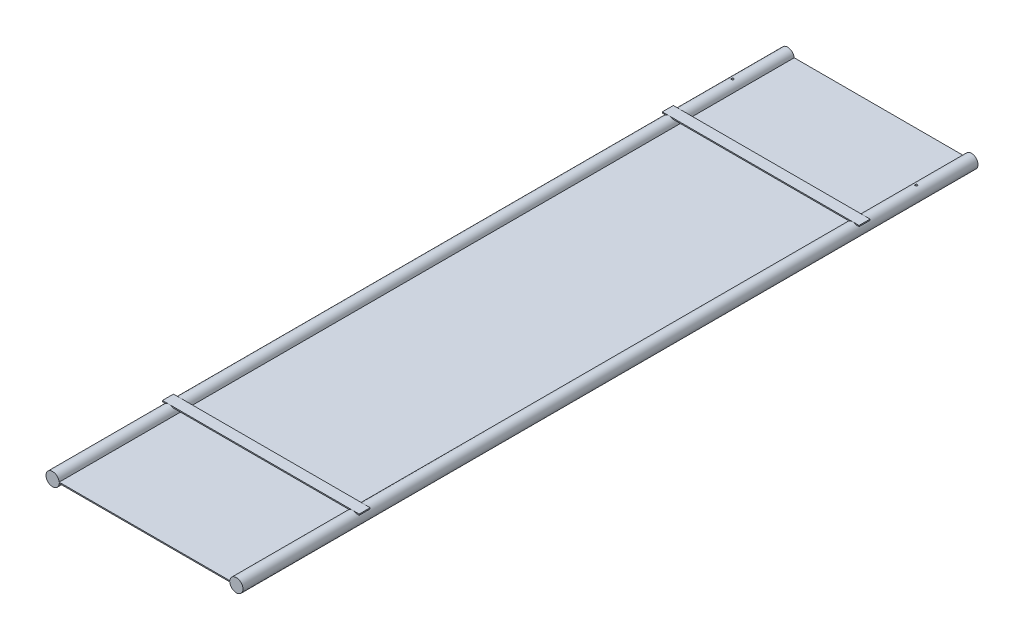
SolidWorks part; units mm, degrees
ref_plane "前视基准面" through (0, 0, 0) normal (0, 0, 1) x (1, 0, 0)
ref_plane "上视基准面" through (0, 0, 0) normal (0, 1, 0) x (1, 0, 0)
ref_plane "右视基准面" through (0, 0, 0) normal (1, 0, 0) x (0, 0, -1)
sketch "草图1" plane through (0, 0, 0) normal (0, 0, 1) x (1, 0, 0)
  line L0 (-250, 0) -> (250, 0) construction
  line L1 (0, 108.6324) -> (0, -184.1552) construction
  circle A0 centre (-250, 0) radius 15
  circle A1 centre (250, 0) radius 15
  dimension "D1" = 30
  dimension "D2" = 30
  dimension "D3" = 250
  dimension "D4" = 500
extrude "凸台-拉伸1" add sketch "草图1" along normal blind 2000
sketch "草图2" plane through (0, 0, 0) normal (0, 0, -1) x (-1, 0, 0)
  line L0 (0, 108.8148) -> (0, -126.0637) construction
  line L1 (-232.0941, 1.8385) -> (232.0941, 1.8385)
  line L2 (-232.0375, -1.1615) -> (232.0375, -1.1615)
  circle A0 centre (-250, 0) radius 15
  arc A1 (-232.0941, 1.8385) -> (-232.0375, -1.1615) centre (-250, 0) ccw
  circle A2 centre (250, 0) radius 15
  arc A3 (232.0941, 1.8385) -> (232.0375, -1.1615) centre (250, 0) cw
  point P10 (0, 1.8385)
  point P14 (0, -1.1615)
  dimension "D1" = 30
  dimension "D2" = 3
  dimension "D3" = 3
extrude "凸台-拉伸2" add sketch "草图2" against normal up to surface (2000 mm away) up to face at (-235, 0, 2000)
sketch "草图3" plane through (0, 1.8385, 0) normal (0, 1, 0) x (1, 0, 0)
  line L0 (268, 0) -> (232.0375, 0) construction
  line L2 (-250.0188, 0) -> (-250.0188, -1.1513) construction
  line L3 (-232.0375, 0) -> (-268, 0) construction
  circle A0 centre (250.0188, -150) radius 3
  circle A1 centre (-250.0188, -150) radius 3
  dimension "D1" = 6
  dimension "D3" = 6
  dimension "D2" = 150
  dimension "D4" = 150
extrude "切除-拉伸1" cut sketch "草图3" against normal through all and the other way through all
ref_plane "基准面1" through (0, 18, 0) normal (0, 1, 0) x (1, 0, 0)
sketch "草图6" plane through (0, 18, 0) normal (0, 1, 0) x (1, 0, 0)
  line L0 (-268, 0) -> (-268, -2000) construction
  line L1 (-268, -293.0238) -> (267.3488, -293.0238)
  line L2 (-268, -293.0238) -> (-268, -323.0238)
  line L3 (-268, -323.0238) -> (267.3488, -323.0238)
  line L4 (267.3488, -293.0238) -> (267.3488, -323.0238)
  line L6 (-268, -1653.1811) -> (267.3488, -1653.1811)
  line L7 (-268, -1653.1811) -> (-268, -1683.1811)
  line L8 (-268, -1683.1811) -> (267.3488, -1683.1811)
  line L9 (267.3488, -1653.1811) -> (267.3488, -1683.1811)
  dimension "D1" = 30
  dimension "D2" = 30
extrude "凸台-拉伸3" add sketch "草图6" against normal blind 3
